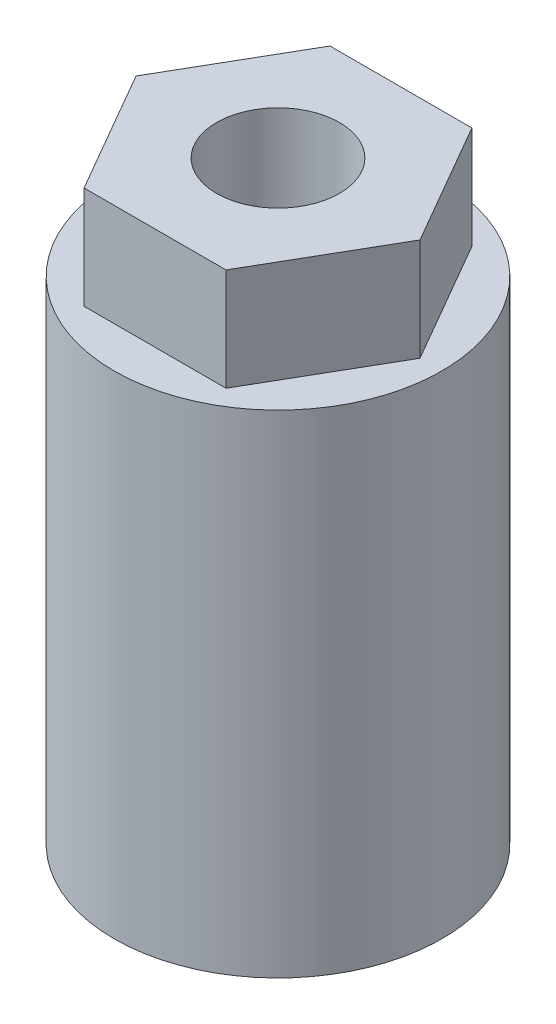
SolidWorks part; units mm, degrees
ref_plane "Front Plane" through (0, 0, 0) normal (0, 0, 1) x (1, 0, 0)
ref_plane "Top Plane" through (0, 0, 0) normal (0, 1, 0) x (1, 0, 0)
ref_plane "Right Plane" through (0, 0, 0) normal (1, 0, 0) x (0, 0, -1)
sketch "Sketch1" plane through (0, 0, 0) normal (0, 0, 1) x (1, 0, 0)
  line L0 (0, 0) -> (0, 16.2128) construction
  line L2 (0, 0) -> (8, 0)
  line L3 (0, 0) -> (0, 12)
  line L4 (0, 12) -> (8, 12)
  line L5 (8, 0) -> (8, 12)
  line L6 (0, 0) -> (4.3, 0)
  line L7 (0, 0) -> (0, 12)
  line L8 (0, 12) -> (4.3, 12)
  line L9 (4.3, 0) -> (4.3, 12)
  line L10 (8, 12) -> (0, 12)
  line L11 (8, 12) -> (8, 24)
  line L12 (8, 24) -> (0, 24)
  line L13 (0, 12) -> (0, 24)
  dimension "D1" = 12
  dimension "D2" = 4.3
  dimension "D3" = 3.7
  dimension "D4" = 12
revolve "Revolve1" add sketch "Sketch1" angle 360 about L0
sketch "Sketch2" plane through (0, 24, 0) normal (0, 1, 0) x (1, 0, 0)
  line L1 (6.9282, 0) -> (3.4641, 6)
  line L2 (3.4641, 6) -> (-3.4641, 6)
  line L3 (-3.4641, 6) -> (-6.9282, 0)
  line L4 (-6.9282, 0) -> (-3.4641, -6)
  line L5 (-3.4641, -6) -> (3.4641, -6)
  line L6 (3.4641, -6) -> (6.9282, 0)
  circle A0 centre (0, 0) radius 6 construction
  dimension "D1" = 12
extrude "Boss-Extrude1" add sketch "Sketch2" along normal blind 5
hole_wizard "Ø6.0mm Dowel Hole1" positions "Sketch3" profile "Sketch4" hole size "Ø6.0" standard "ANSI Metric"
sketch "Sketch3" plane through (0, 29, 0) normal (0, 1, 0) x (1, 0, 0)
  point P0 (0, 0)
sketch "Sketch4" plane through (0, 29, 0) normal (1, 0, 0) x (0, 0, 1)
  line L0 (0, 0) -> (0, 11.8026)
  line L1 (0, 11.8026) -> (3, 10)
  line L2 (3, 10) -> (3, 0)
  line L5 (3, 0) -> (0, 0)
  line L10 (0, 11.8026) -> (-3, 10) construction
  line L11 (0, -6.35) -> (0, 107.95) construction
  dimension "Hole Dia." = 6
  dimension "Hole Depth" = 10
  dimension "Drill Angle" = 118
sketch "Sketch5" plane through (0, 0, 0) normal (0, -1, 0) x (1, 0, 0)
  line L1 (2.55, -1.75) -> (6.05, -1.75)
  line L2 (2.55, -1.75) -> (2.55, 1.75)
  line L3 (2.55, 1.75) -> (6.05, 1.75)
  line L4 (6.05, -1.75) -> (6.05, 1.75)
  line L5 (2.55, -1.75) -> (6.05, 1.75) construction
  line L6 (2.55, 1.75) -> (6.05, -1.75) construction
  circle A0 centre (0, 0) radius 4.3 construction
  point P0 (4.3, 0)
  dimension "D1" = 3.5
  dimension "D2" = 3.5
extrude "Cut-Extrude1" cut sketch "Sketch5" against normal up to surface (12 mm away)
